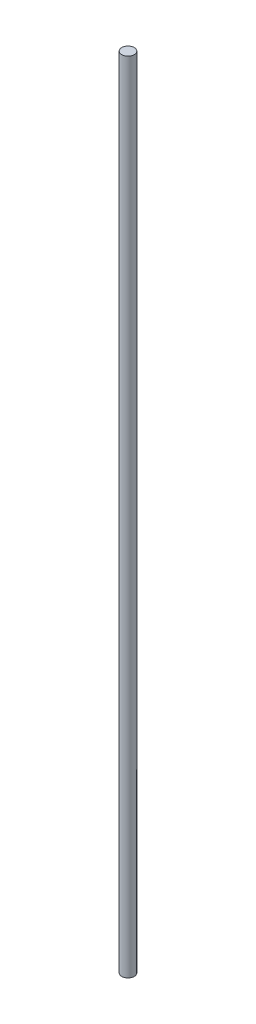
SolidWorks part; units mm, degrees
ref_plane "Front Plane" through (0, 0, 0) normal (0, 0, 1) x (1, 0, 0)
ref_plane "Top Plane" through (0, 0, 0) normal (0, 1, 0) x (1, 0, 0)
ref_plane "Right Plane" through (0, 0, 0) normal (1, 0, 0) x (0, 0, -1)
sketch "Sketch1" plane through (0, 0, 0) normal (0, 1, 0) x (1, 0, 0)
  circle A0 centre (0, 0) radius 5
  dimension "D1" = 10
extrude "Boss-Extrude1" add sketch "Sketch1" along normal blind 640
